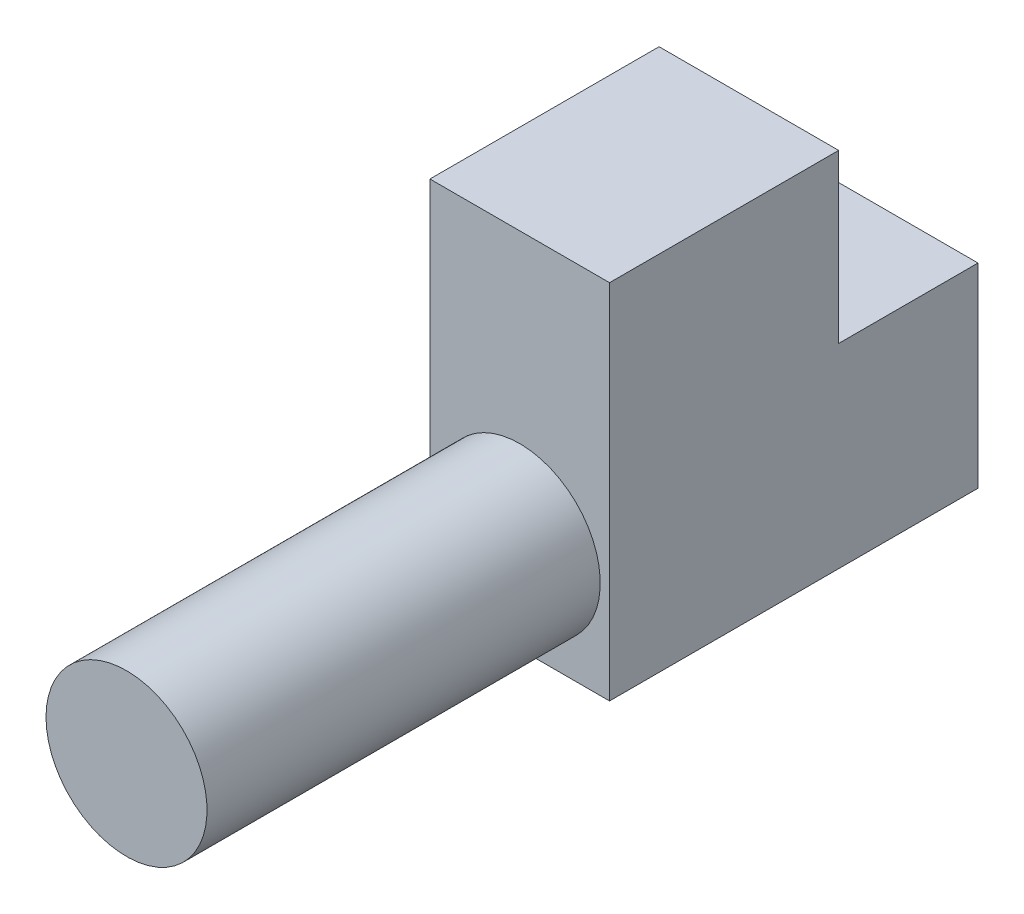
SolidWorks part; units mm, degrees
ref_plane "Front Plane" through (0, 0, 0) normal (0, 0, 1) x (1, 0, 0)
ref_plane "Top Plane" through (0, 0, 0) normal (0, 1, 0) x (1, 0, 0)
ref_plane "Right Plane" through (0, 0, 0) normal (1, 0, 0) x (0, 0, -1)
sketch "Sketch1" plane through (0, 0, 0) normal (0, 0, 1) x (1, 0, 0)
  line L1 (-14.5, -15.75) -> (14.5, -15.75)
  line L2 (-14.5, -15.75) -> (-14.5, 15.75)
  line L3 (-14.5, 15.75) -> (14.5, 15.75)
  line L4 (14.5, -15.75) -> (14.5, 15.75)
  line L5 (-14.5, -15.75) -> (14.5, 15.75) construction
  line L6 (-14.5, 15.75) -> (14.5, -15.75) construction
  point P0 (0, 0)
extrude "Boss-Extrude1" add sketch "Sketch1" along normal blind 59.5
sketch "Sketch2" plane through (0, 0, 0) normal (0, 1, 0) x (1, 0, 0)
  line L0 (0, 0) -> (0, -22.5) construction
  line L1 (0, -22.5) -> (0, -41) construction
  line L2 (14.5, -59.5) -> (14.5, 0) construction
  line L3 (-14.5, -59.5) -> (14.5, -59.5)
  line L4 (-14.5, -59.5) -> (-14.5, -22.5)
  line L5 (-14.5, -22.5) -> (14.5, -22.5)
  line L6 (14.5, -59.5) -> (14.5, -22.5)
  line L7 (-14.5, -59.5) -> (14.5, -22.5) construction
  line L8 (-14.5, -22.5) -> (14.5, -59.5) construction
extrude "Boss-Extrude2" add sketch "Sketch2" along normal blind 27 from surface at 15.75 starting at face at (0, 15.75, 29.75)
sketch "Sketch4" plane through (0, 0, 0) normal (0, 0, 1) x (1, 0, 0)
  line L0 (-14.5, 15.75) -> (-14.5, -15.75) construction
  line L1 (-14.5, 15.75) -> (-14.5, -15.75) construction
  line L2 (14.5, 15.75) -> (-14.5, 15.75) construction
  line L3 (-14.5, 0) -> (14.5, 0) construction
  line L4 (14.5, -15.75) -> (14.5, 42.75) construction
  circle A0 centre (0, 0) radius 13
extrude "Boss-Extrude3" add sketch "Sketch4" along normal blind 63.5 from surface at 59.5 starting at face at (0, 13.5, 59.5)
